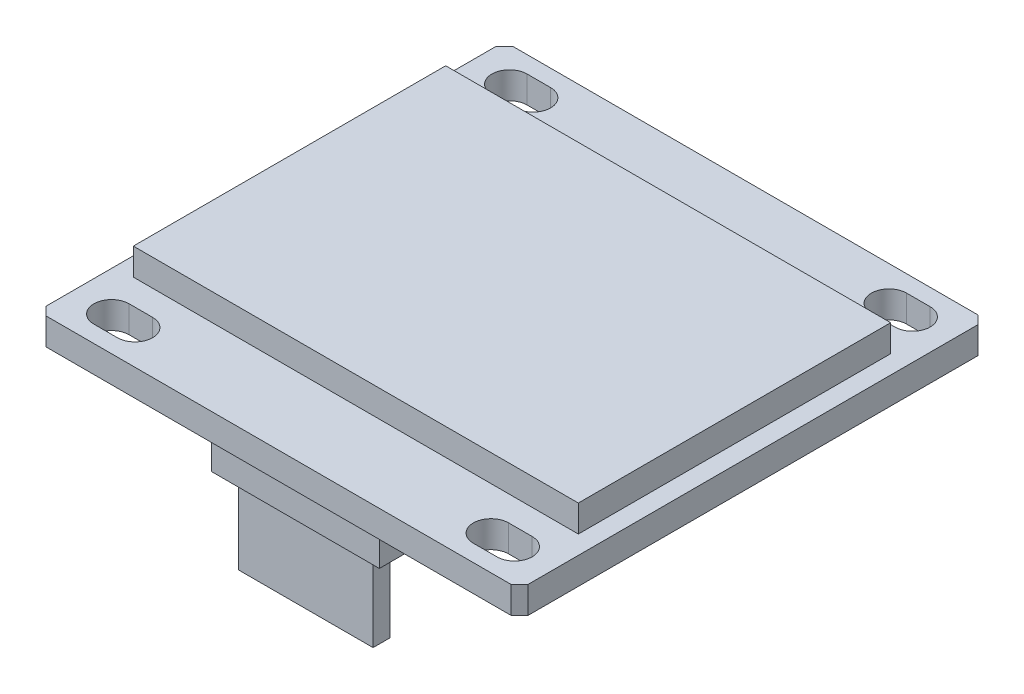
SolidWorks part; units mm, degrees
ref_plane "前视基准面" through (0, 0, 0) normal (0, 0, 1) x (1, 0, 0)
ref_plane "上视基准面" through (0, 0, 0) normal (0, 1, 0) x (1, 0, 0)
ref_plane "右视基准面" through (0, 0, 0) normal (1, 0, 0) x (0, 0, -1)
sketch "草图1" plane through (0, 0, 0) normal (0, 1, 0) x (1, 0, 0)
  line L1 (-14.35, -13.9) -> (14.35, -13.9)
  line L2 (-14.35, -13.9) -> (-14.35, 13.9)
  line L3 (-14.35, 13.9) -> (14.35, 13.9)
  line L4 (14.35, -13.9) -> (14.35, 13.9)
  line L5 (-14.35, -13.9) -> (14.35, 13.9) construction
  line L6 (-14.35, 13.9) -> (14.35, -13.9) construction
  point P0 (0, 0)
  dimension "D1" = 28.7
  dimension "D2" = 27.8
extrude "凸台-拉伸1" add sketch "草图1" along normal blind 1.6
sketch "草图2" plane through (0, 1.6, 0) normal (0, 1, 0) x (1, 0, 0)
  line L1 (-13.25, -9.3) -> (13.25, -9.3)
  line L2 (-13.25, -9.3) -> (-13.25, 9.3)
  line L3 (-13.25, 9.3) -> (13.25, 9.3)
  line L4 (13.25, -9.3) -> (13.25, 9.3)
  line L5 (-13.25, -9.3) -> (13.25, 9.3) construction
  line L6 (-13.25, 9.3) -> (13.25, -9.3) construction
  point P0 (0, 0)
  point P7 (0, 0)
  point P8 (0, 0)
  point P11 (0, 0)
  dimension "D1" = 18.6
  dimension "D2" = 26.5
extrude "凸台-拉伸2" add sketch "草图2" along normal blind 1.6
sketch "草图3" plane through (0, 1.6, 0) normal (0, 1, 0) x (1, 0, 0)
  line L0 (0, 13.9) -> (0, -15.8038) construction
  line L1 (14.35, 13.9) -> (-14.35, 13.9) construction
  line L2 (-14.35, 0) -> (16.2376, 0) construction
  line L3 (-14.35, 13.9) -> (-14.35, -13.9) construction
  line L4 (-12, 11.85) -> (-10.6, 11.85) construction
  line L5 (-12, 12.9) -> (-10.6, 12.9)
  line L6 (-12, 10.8) -> (-10.6, 10.8)
  line L7 (12, 11.85) -> (10.6, 11.85) construction
  line L8 (12, 12.9) -> (10.6, 12.9)
  line L9 (12, 10.8) -> (10.6, 10.8)
  line L10 (12, -11.85) -> (10.6, -11.85) construction
  line L11 (12, -12.9) -> (10.6, -12.9)
  line L12 (12, -10.8) -> (10.6, -10.8)
  line L13 (-12, -11.85) -> (-10.6, -11.85) construction
  line L14 (-12, -12.9) -> (-10.6, -12.9)
  line L15 (-12, -10.8) -> (-10.6, -10.8)
  arc A0 (-12, 12.9) -> (-12, 10.8) centre (-12, 11.85) ccw
  arc A1 (-10.6, 10.8) -> (-10.6, 12.9) centre (-10.6, 11.85) ccw
  arc A2 (12, 12.9) -> (12, 10.8) centre (12, 11.85) cw
  arc A3 (10.6, 10.8) -> (10.6, 12.9) centre (10.6, 11.85) cw
  arc A4 (12, -12.9) -> (12, -10.8) centre (12, -11.85) ccw
  arc A5 (10.6, -10.8) -> (10.6, -12.9) centre (10.6, -11.85) ccw
  arc A6 (-12, -12.9) -> (-12, -10.8) centre (-12, -11.85) cw
  arc A7 (-10.6, -10.8) -> (-10.6, -12.9) centre (-10.6, -11.85) cw
  point P11 (-11.3, 11.85)
  point P18 (11.3, 11.85)
  point P25 (11.3, -11.85)
  point P32 (-11.3, -11.85)
  dimension "D4" = 22.6
  dimension "D1" = 2.1
  dimension "D2" = 1.4
  dimension "D3" = 1
extrude "切除-拉伸1" cut sketch "草图3" against normal through all
chamfer "倒角1" distance 0.5 angle 45 4 edges at (-14.35, 0.8, 13.9) (14.35, 0.8, 13.9) (-14.35, 0.8, -13.9) (14.35, 0.8, -13.9)
sketch "草图4" plane through (0, 0, 0) normal (0, -1, 0) x (1, 0, 0)
  line L0 (-13.85, 13.9) -> (13.85, 13.9) construction
  line L1 (-5, 10.4) -> (5, 10.4)
  line L2 (-5, 10.4) -> (-5, 12.9)
  line L3 (-5, 12.9) -> (5, 12.9)
  line L4 (5, 10.4) -> (5, 12.9)
  line L5 (-5, 10.4) -> (5, 12.9) construction
  line L6 (-5, 12.9) -> (5, 10.4) construction
  point P0 (0, 11.65)
  point P5 (0, 0)
  dimension "D1" = 10
  dimension "D2" = 2.5
  dimension "D3" = 1
extrude "凸台-拉伸3" add sketch "草图4" along normal blind 2.5
sketch "草图5" plane through (0, -2.5, 0) normal (0, -1, 0) x (1, 0, 0)
  line L1 (-4.1032, 11.1694) -> (3.8968, 11.1694)
  line L2 (-4.1032, 11.1694) -> (-4.1032, 12.1694)
  line L3 (-4.1032, 12.1694) -> (3.8968, 12.1694)
  line L4 (3.8968, 11.1694) -> (3.8968, 12.1694)
  line L5 (-4.1032, 11.1694) -> (3.8968, 12.1694) construction
  line L6 (-4.1032, 12.1694) -> (3.8968, 11.1694) construction
  point P0 (-0.1032, 11.6694)
  dimension "D1" = 8
  dimension "D2" = 1
extrude "凸台-拉伸4" add sketch "草图5" along normal blind 5
